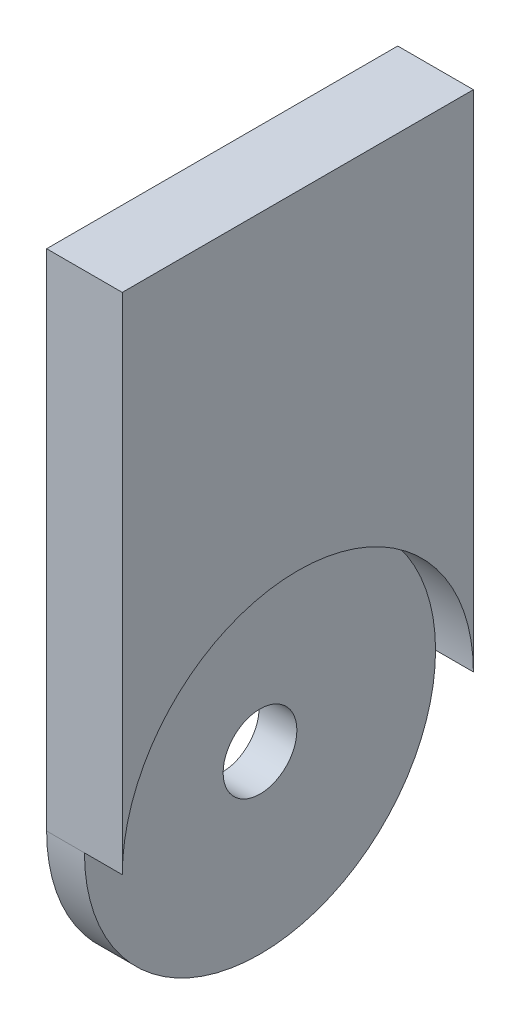
SolidWorks part; units mm, degrees
ref_plane "Plan de face" through (0, 0, 0) normal (0, 0, 1) x (1, 0, 0)
ref_plane "Plan de dessus" through (0, 0, 0) normal (0, 1, 0) x (1, 0, 0)
ref_plane "Plan de droite" through (0, 0, 0) normal (1, 0, 0) x (0, 0, -1)
sketch "Esquisse1" plane through (0, 0, 0) normal (1, 0, 0) x (0, 0, -1)
  line L1 (-15.3655, 38.894) -> (12.4845, 38.894)
  line L2 (-15.3655, 38.894) -> (-15.3655, -1.106)
  line L3 (-15.3655, -1.106) -> (12.4845, -1.106)
  line L4 (12.4845, 38.894) -> (12.4845, -1.106)
  arc A0 (12.4845, -1.106) -> (-15.3655, -1.106) centre (-1.4405, -1.106) cw
  dimension "D1" = 27.85
  dimension "D2" = 40
extrude "Boss.-Extru.1" add sketch "Esquisse1" along normal blind 6 contours L4 L1 L2 L3 | A0 L3
sketch "Esquisse2" plane through (6, 0, 0) normal (1, 0, 0) x (0, 0, -1)
  circle A0 centre (-1.4405, -1.106) radius 13.925
extrude "Enlèv. mat.-Extru.1" cut sketch "Esquisse2" against normal blind 3
sketch "Esquisse3" plane through (0, 0, 0) normal (-1, 0, 0) x (0, 0, 1)
  circle A0 centre (1.4405, -1.106) radius 2.925
  dimension "D1" = 5.85
extrude "Enlèv. mat.-Extru.2" cut sketch "Esquisse3" against normal blind 10
